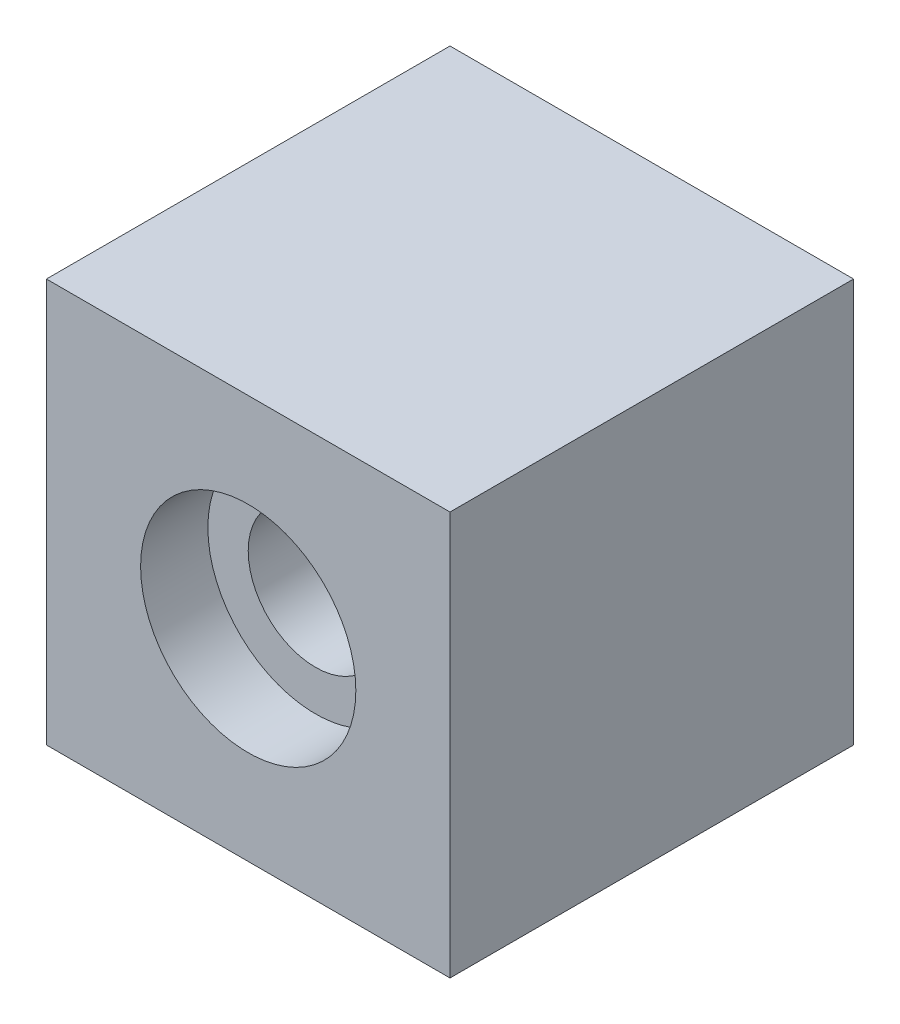
SolidWorks part; units mm, degrees
material "ABS"
ref_plane "前基準面" through (0, 0, 0) normal (0, 0, 1) x (1, 0, 0)
ref_plane "上基準面" through (0, 0, 0) normal (0, 1, 0) x (1, 0, 0)
ref_plane "右基準面" through (0, 0, 0) normal (1, 0, 0) x (0, 0, -1)
sketch "草圖1" plane through (0, 0, 0) normal (0, 0, 1) x (1, 0, 0)
  line L0 (0, 0) -> (30, 30) construction
  line L1 (0, 0) -> (30, 0)
  line L2 (0, 0) -> (0, 30)
  line L3 (0, 30) -> (30, 30)
  line L4 (30, 0) -> (30, 30)
  circle A0 centre (15, 15) radius 5
  dimension "D1" = 10
  dimension "D2" = 30
  dimension "D3" = 30
extrude "填料-伸長1" add sketch "草圖1" along normal mid plane 30
sketch "草圖2" plane through (0, 30, 0) normal (0, 1, 0) x (1, 0, 0)
  line L0 (30, 15) -> (0, -15) construction
  circle A0 centre (15, 0) radius 7.8454
sketch "草圖3" plane through (0, 0, 15) normal (0, 0, 1) x (1, 0, 0)
  circle A0 centre (15, 15) radius 8
  dimension "D1" = 16
extrude "除料-伸長1" cut sketch "草圖3" against normal blind 5
mirror "鏡射1" about plane through (0, 0, 0) normal (0, 0, 1) of "除料-伸長1"
